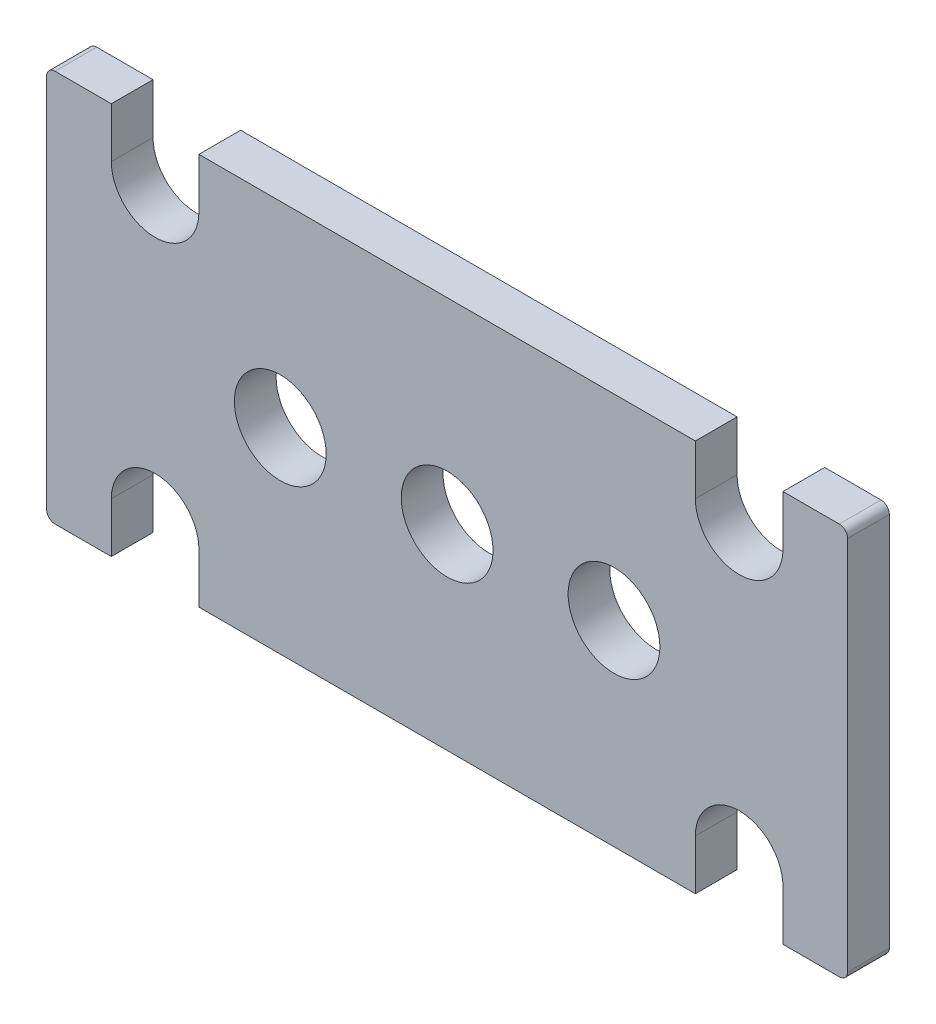
SolidWorks part; units mm, degrees
ref_plane "前视基准面" through (0, 0, 0) normal (0, 0, 1) x (1, 0, 0)
ref_plane "上视基准面" through (0, 0, 0) normal (0, 1, 0) x (1, 0, 0)
ref_plane "右视基准面" through (0, 0, 0) normal (1, 0, 0) x (0, 0, -1)
other "Configuration Table"
sketch "草图1" plane through (0, 0, 0) normal (0, 0, 1) x (1, 0, 0)
  line L0 (0, 0) -> (96, 0)
  line L1 (96, 0) -> (96, -47)
  line L2 (96, -47) -> (0, -47)
  line L3 (0, -47) -> (0, 0)
  dimension "D1" = 96
  dimension "D2" = 47
extrude "凸台-拉伸1" add sketch "草图1" along normal blind 5
sketch "草图2" plane through (0, 0, 5) normal (0, 0, 1) x (1, 0, 0)
  line L0 (96, -23.5) -> (0, -23.5)
  line L1 (96, -47) -> (96, 0) construction
  line L2 (0, 0) -> (0, -47) construction
  line L3 (48, 0) -> (48, -47)
  line L4 (96, 0) -> (0, 0) construction
  line L5 (0, -47) -> (96, -47) construction
  line L6 (48, -23.5) -> (48, -12)
  line L7 (77.75, -6) -> (77.75, 0)
  line L8 (88.25, -6) -> (88.25, 0)
  line L9 (88.25, 0) -> (77.75, 0)
  line L10 (77.75, 0) -> (88.25, 0)
  line L11 (18.25, -6) -> (18.25, 0)
  line L12 (7.75, -6) -> (7.75, 0)
  line L13 (7.75, 0) -> (18.25, 0)
  line L14 (88.25, -41) -> (88.25, -47)
  line L15 (88.25, -47) -> (77.75, -47)
  line L16 (77.75, -41) -> (77.75, -47)
  line L17 (7.75, -41) -> (7.75, -47)
  line L18 (7.75, -47) -> (18.25, -47)
  line L19 (18.25, -41) -> (18.25, -47)
  circle A0 centre (83, -6) radius 5.25
  circle A1 centre (83, -41) radius 5.25
  circle A2 centre (13, -41) radius 5.25
  circle A3 centre (13, -6) radius 5.25
  line M5 (0, -47) -> (96, -47)
  line M7 (96, 0) -> (0, 0)
  dimension "D1" = 35
  dimension "D3" = 10.5
  dimension "D2" = 17.5
fillet "圆角1" radius 1 4 edges at (96, -47, 2.5) (0, -47, 2.5) (0, 0, 2.5) (96, 0, 2.5)
sketch "草图8" plane through (0, 0, 5) normal (0, 0, 1) x (1, 0, 0)
  line L5 (48, -47) -> (48, 0)
  line L6 (1, -47) -> (95, -47) construction
  line L7 (95, 0) -> (1, 0) construction
  line L8 (96, -23.5) -> (0, -23.5)
  line L9 (96, -46) -> (96, -1) construction
  line L10 (0, -1) -> (0, -46) construction
  line L11 (48, -23.5) -> (78, -23.5)
  line L12 (48, -23.5) -> (18, -23.5)
  circle A1 centre (48, -23.5) radius 5.5
  circle A3 centre (68, -23.5) radius 5.5
  circle A4 centre (28, -23.5) radius 5.5
  dimension "D3" = 20
  dimension "D2" = 60
  dimension "D4" = 20
extrude "切除-拉伸2" cut sketch "草图8" against normal blind 10 contours L8 A4 | L8 A4 | L8 A1 L5 | L5 A1 L8 | L11 A1 L5 | L5 A1 L11 | L11 A3 | L11 A3
extrude "切除-拉伸3" cut sketch "草图2" against normal blind 10 contours A0 | A3 | A2 | A1 | L12 A3 L11 M7 | A2 L17 L19 M5 | L14 A1 L16 M5 | A0 L8 L7 M7
